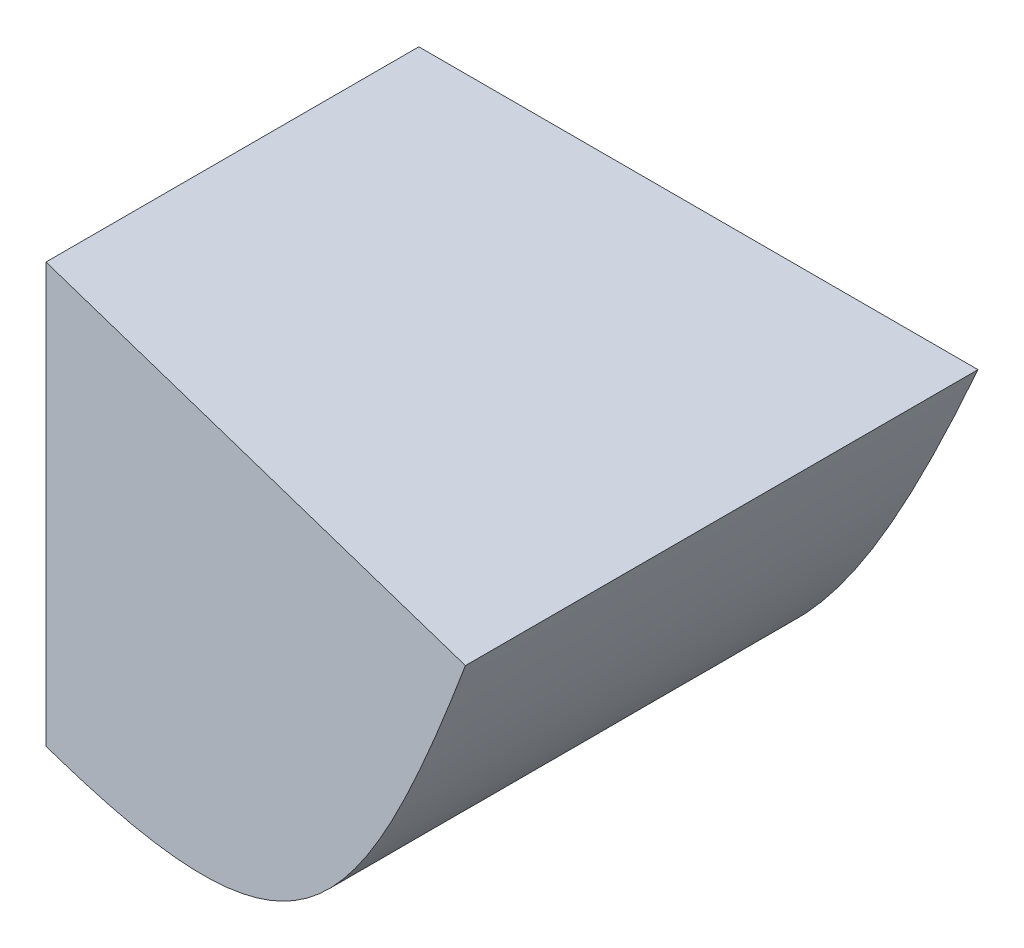
SolidWorks part; units mm, degrees
ref_plane "Front Plane" through (0, 0, 0) normal (0, 0, 1) x (1, 0, 0)
ref_plane "Top Plane" through (0, 0, 0) normal (0, 1, 0) x (1, 0, 0)
ref_plane "Right Plane" through (0, 0, 0) normal (1, 0, 0) x (0, 0, -1)
ref_plane "plane:profile" through (0, 0, 0) normal (0, 0, 1) x (1, 0, 0)
sketch "profile:rational" plane through (0, 0, 0) normal (0, 0, 1) x (1, 0, 0)
  line L0 (12, 9) -> (0, 9)
  line L1 (0, 9) -> (0, 0)
  spline S0 degree 3 poles (0, 0) (4, 0) (8, 0) (12, 9) knots 0 0 0 0 1 1 1 1 weights 1 0.75 1.25 1
extrude "feature:prism" add sketch "profile:rational" along normal blind 14 separate body
ref_plane "plane:cut" through (0, 20, 0) normal (0, -1, 0) x (1, 0, 0)
sketch "profile:cut" plane through (0, 20, 0) normal (0, -1, 0) x (1, 0, 0)
  line L0 (-2, 7.5) -> (14, 11.5)
  line L1 (14, 11.5) -> (14, 20)
  line L2 (14, 20) -> (-2, 20)
  line L3 (-2, 20) -> (-2, 7.5)
extrude "feature:trim" cut sketch "profile:cut" along normal through all
